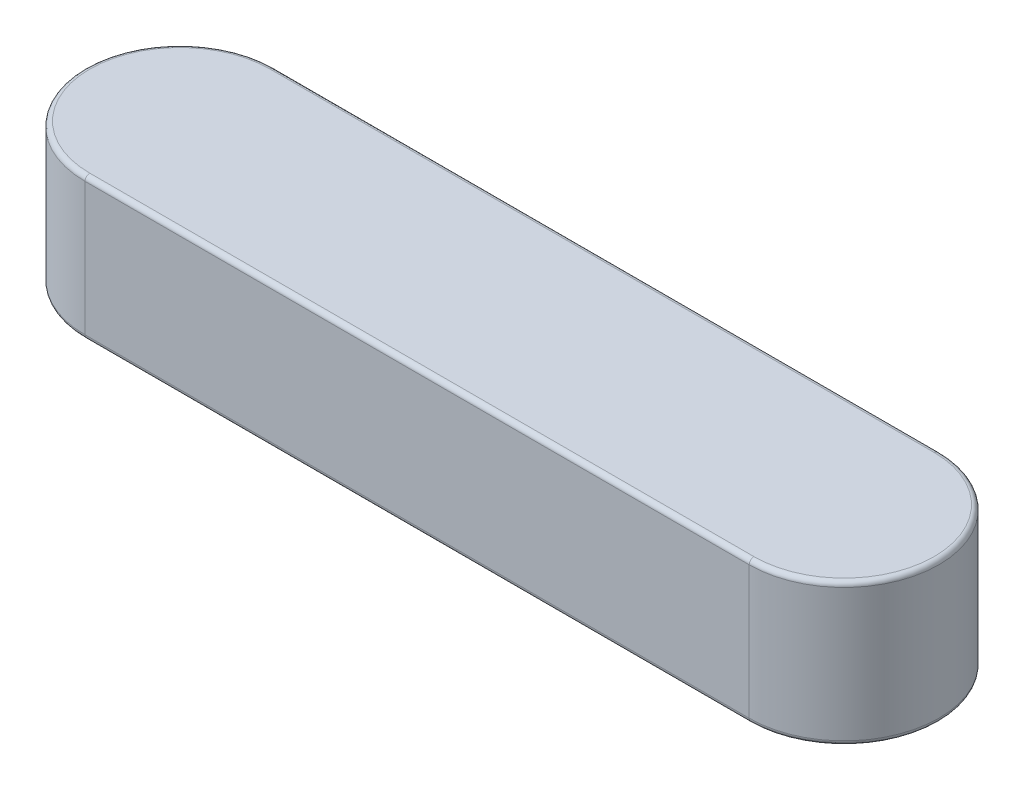
SolidWorks part; units mm, degrees
material "1060 Alloy"
ref_plane "Front Plane" through (0, 0, 0) normal (0, 0, 1) x (1, 0, 0)
ref_plane "Top Plane" through (0, 0, 0) normal (0, 1, 0) x (1, 0, 0)
ref_plane "Right Plane" through (0, 0, 0) normal (1, 0, 0) x (0, 0, -1)
sketch "Sketch1" plane through (0, 0, 0) normal (0, 1, 0) x (1, 0, 0)
  line L0 (-13.6061, 0) -> (14.3939, 0) construction
  line L1 (-13.6061, 4) -> (14.3939, 4)
  line L2 (-13.6061, -4) -> (14.3939, -4)
  arc A0 (-13.6061, 4) -> (-13.6061, -4) centre (-13.6061, 0) ccw
  arc A1 (14.3939, -4) -> (14.3939, 4) centre (14.3939, 0) ccw
  point P3 (0.3939, 0)
  dimension "D2" = 4
  dimension "D1" = 28
extrude "Boss-Extrude1" add sketch "Sketch1" along normal blind 6
fillet "Fillet1" radius 0.2 8 edges at (0.3939, 0, -4) (18.3939, 0, 0) (0.3939, 0, 4) (-17.6061, 6, 0) (0.3939, 6, -4) (18.3939, 6, 0) (-17.6061, 0, 0) (0.3939, 6, 4)
